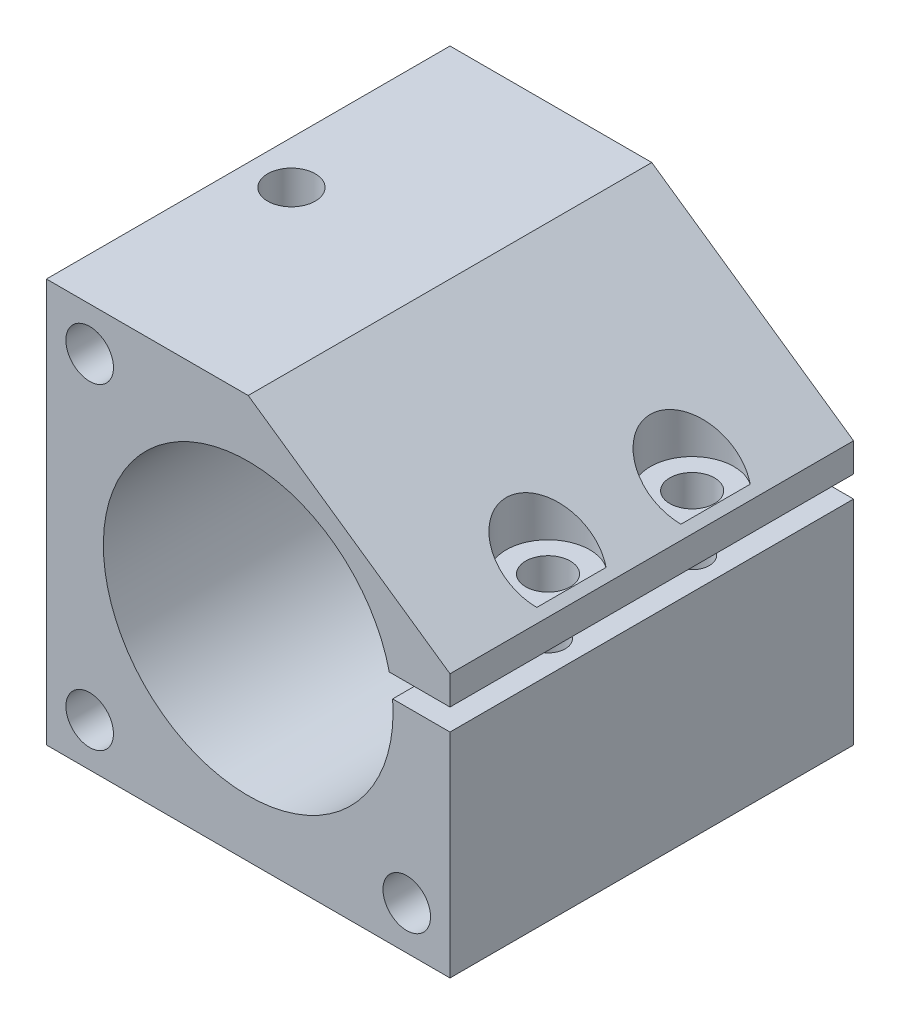
SolidWorks part; units mm, degrees
material "7075-T6 (SN)"
ref_plane "Plan de face" through (0, 0, 0) normal (0, 0, 1) x (1, 0, 0)
ref_plane "Plan de dessus" through (0, 0, 0) normal (0, 1, 0) x (1, 0, 0)
ref_plane "Plan de droite" through (0, 0, 0) normal (1, 0, 0) x (0, 0, -1)
sketch "Esquisse1" plane through (0, 0, 0) normal (0, 0, 1) x (1, 0, 0)
  line L0 (0, 14) -> (14, 4.2799)
  line L1 (14, 4.2799) -> (14, -14) construction
  line L3 (0, 0) -> (14, 0) construction
  line L4 (14, 4.2799) -> (14, 2.2799)
  line L5 (14, 2.2799) -> (9.788, 2.2799)
  line L6 (14, 0.7799) -> (14, -14)
  line L7 (14, 0.7799) -> (10.0197, 0.7799)
  line L9 (-14, -14) -> (-14, 14)
  line L11 (-14, 14) -> (0, 0) construction
  line L12 (0, 0) -> (0, 14) construction
  line L13 (-14, 14) -> (0, 14)
  line L14 (-14, -14) -> (14, -14)
  line L15 (0, 0) -> (-14, 0) construction
  line L16 (-11, 11) -> (-11, -11) construction
  line L17 (-11, -11) -> (11, -11) construction
  circle A0 centre (0, 0) radius 10.05 construction
  arc A3 (9.788, 2.2799) -> (10.0197, 0.7799) centre (0, 0) ccw
  circle A6 centre (-11, 11) radius 1.65
  circle A7 centre (-11, -11) radius 1.65
  circle A8 centre (11, -11) radius 1.65
  circle A9 centre (0, 0) radius 11.5 construction
  dimension "D1" = 28
  dimension "D2" = 20.1
  dimension "D7" = 23
  dimension "D8" = 3.3
  dimension "D3" = 28
  dimension "D4" = 14
  dimension "D5" = 1.5
  dimension "D6" = 2
  dimension "D9" = 19.799
  dimension "D10" = 3
  dimension "D11" = 14
extrude "Boss.-Extru.1" add sketch "Esquisse1" along normal blind 28
ref_plane "Plan2" through (0, 2.2799, 0) normal (0, -1, 0) x (-1, 0, 0)
sketch "Esquisse6" plane through (0, 2.2799, 0) normal (0, -1, 0) x (-1, 0, 0)
  line L0 (-11.8, -9) -> (-11.8, -19) construction
  line L1 (-14, -28) -> (-14, 0) construction
  line L2 (-14, -14) -> (-11.8, -14) construction
  line L5 (-14, -28) -> (-14, 0) construction
  circle A0 centre (-11.8, -9) radius 2.9
  circle A1 centre (-11.8, -19) radius 2.9
  dimension "D2" = 5.8
  dimension "D1" = 2.2
  dimension "D3" = 10
extrude "Enlèv. mat.-Extru.3" cut sketch "Esquisse6" against normal through all from offset 2.4 offset against normal yes
sketch "Esquisse7" plane through (0, 4.6799, 0) normal (0, 1, 0) x (1, 0, 0)
  circle A0 centre (11.8, -9) radius 1.55
  circle A1 centre (11.8, -19) radius 1.55
  dimension "D1" = 3.1
extrude "Enlèv. mat.-Extru.4" cut sketch "Esquisse7" against normal up to vertex (3.9 mm away) up to point (14, 0.7799, 28)
sketch "Esquisse8" plane through (0, 0.7799, 0) normal (0, 1, 0) x (1, 0, 0)
  circle A0 centre (11.8, -9) radius 1.2
  circle A1 centre (11.8, -19) radius 1.2
  dimension "D1" = 2.4
extrude "Enlèv. mat.-Extru.5" cut sketch "Esquisse8" against normal blind 10 and the other way through all
sketch "Esquisse10" plane through (0, 0, 28) normal (0, 0, 1) x (1, 0, 0)
  circle A1 centre (-11, -11) radius 1.65
  circle A2 centre (11, -11) radius 1.65
  circle A3 centre (-11, 11) radius 1.65
  circle A4 centre (-11, 11) radius 1.65 construction
  circle A5 centre (-11, -11) radius 1.65 construction
  circle A6 centre (11, -11) radius 1.65 construction
extrude "Boss.-Extru.6" add sketch "Esquisse10" against normal blind 6 from offset 11 offset against normal yes
sketch "Esquisse11" plane through (0, -14, 0) normal (0, 1, 0) x (1, 0, 0)
  line L0 (-11, 0) -> (-11, -28) construction
  line L1 (0, 0) -> (-14, 0) construction
  line L2 (0, -28) -> (-14, -28) construction
  line L3 (-14, -28) -> (-14, 0) construction
  line L4 (0, -28) -> (0, 0) construction
  line L5 (-14, -28) -> (14, -28) construction
  line L6 (-14, 0) -> (14, 0) construction
  line L7 (-14, -14) -> (14, -14) construction
  line L8 (14, -28) -> (14, 0) construction
  circle A0 centre (-11, -14) radius 1.65
  circle A1 centre (11, -14) radius 1.65
  dimension "D2" = 3.3
  dimension "D1" = 3
extrude "Enlèv. mat.-Extru.6" cut sketch "Esquisse11" along normal blind 10
sketch "Esquisse12" plane through (0, 14, 0) normal (0, 1, 0) x (1, 0, 0)
  line L0 (-14, -14) -> (14, -14) construction
  line L1 (-14, -28) -> (-14, 0) construction
  line L2 (14, -28) -> (14, 0) construction
  circle A0 centre (-11, -14) radius 1.65
  dimension "D1" = 3.3
  dimension "D2" = 3
extrude "Enlèv. mat.-Extru.7" cut sketch "Esquisse12" against normal blind 10
sketch "Esquisse13" plane through (14, 0, 0) normal (1, 0, 0) x (0, 0, -1)
  line L0 (-28, -11) -> (0, -11) construction
  line L1 (-28, -14) -> (-28, 0.7799) construction
  line L2 (0, -14) -> (0, 0.7799) construction
  line L3 (-28, -14) -> (0, -14) construction
  circle A0 centre (-14, -11) radius 1.65
  dimension "D1" = 3.3
  dimension "D2" = 3
